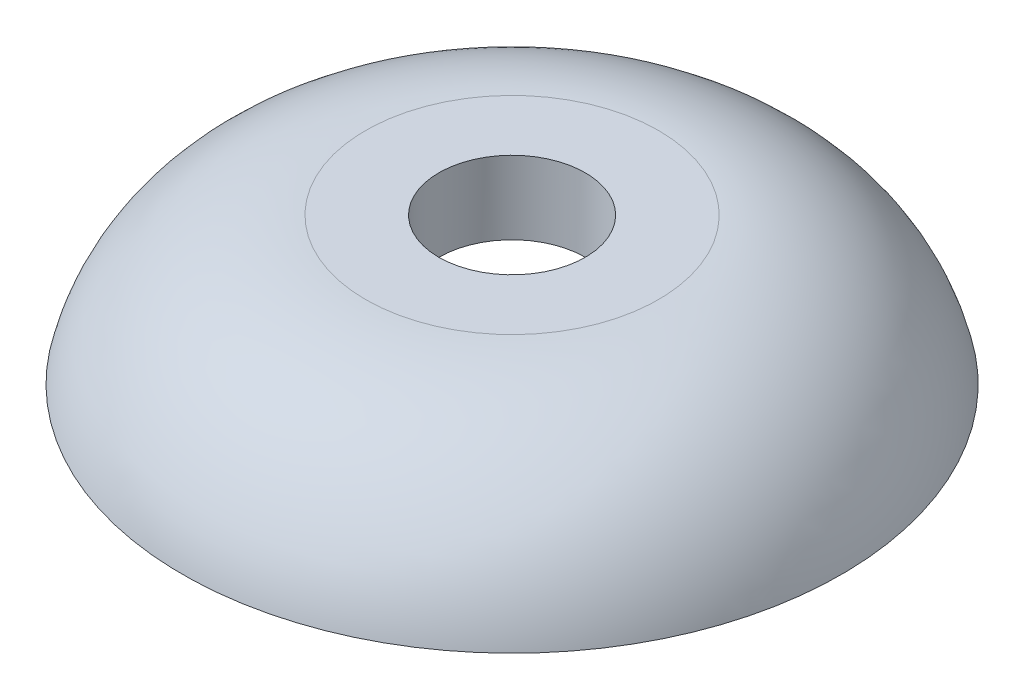
SolidWorks part; units mm, degrees
ref_plane "Plano frontal" through (0, 0, 0) normal (0, 0, 1) x (1, 0, 0)
ref_plane "Plano superior" through (0, 0, 0) normal (0, 1, 0) x (1, 0, 0)
ref_plane "Plano direito" through (0, 0, 0) normal (1, 0, 0) x (0, 0, -1)
sketch "Esboço1" plane through (0, 0, 0) normal (0, 0, 1) x (1, 0, 0)
  line L0 (0, 0) -> (0, 4)
  line L1 (9, 0) -> (0, 0)
  line L2 (0, 4) -> (4, 4)
  arc A1 (4, 4) -> (9, 0) centre (4, -1.125) cw
  dimension "D1" = 9
  dimension "D2" = 4
  dimension "D3" = 4
revolve "Revolução1" add sketch "Esboço1" angle 360 about L0
sketch "Esboço2" plane through (0, 4, 0) normal (0, 1, 0) x (1, 0, 0)
  circle A0 centre (0, 0) radius 2
  dimension "D1" = 4
extrude "Corte-extrusão1" cut sketch "Esboço2" against normal blind 10
sketch "Esboço3" plane through (0, 0, 0) normal (0, -1, 0) x (1, 0, 0)
  circle A0 centre (0, 0) radius 5.25
  dimension "D1" = 10.5
extrude "Corte-extrusão2" cut sketch "Esboço3" against normal blind 2
fillet "Filete1" radius 1.5 1 edges at (0, 2, -5.25)
